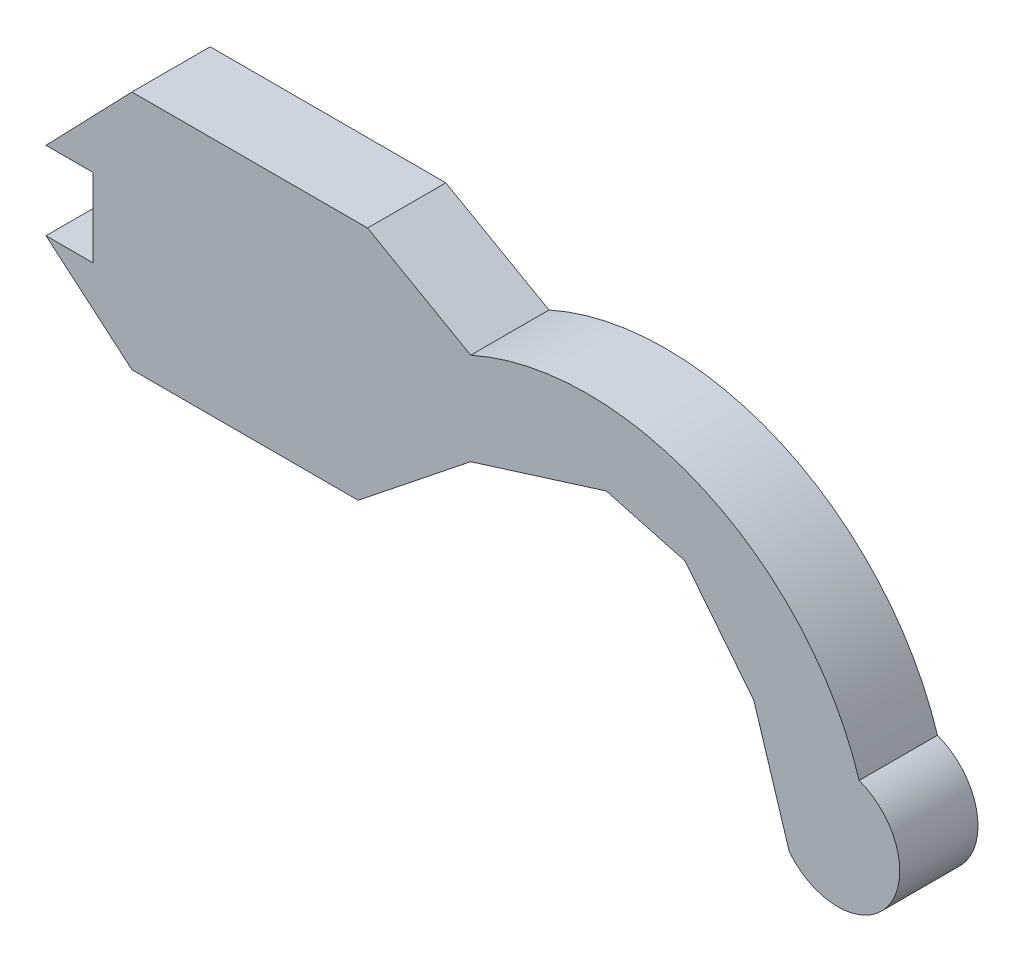
SolidWorks part; units mm, degrees
ref_plane "Front Plane" through (0, 0, 0) normal (0, 0, 1) x (1, 0, 0)
ref_plane "Top Plane" through (0, 0, 0) normal (0, 1, 0) x (1, 0, 0)
ref_plane "Right Plane" through (0, 0, 0) normal (1, 0, 0) x (0, 0, -1)
sketch "Sketch1" plane through (0, 0, 0) normal (0, 0, 1) x (1, 0, 0)
  line L0 (8.8809, 0) -> (7.9628, 0)
  line L1 (7.9628, 0) -> (9.6353, -1.4227)
  line L2 (9.6353, -1.4227) -> (14.04, -1.4227)
  line L3 (14.04, -1.4227) -> (16.2316, 0.3239)
  line L4 (16.2316, 0.3239) -> (18.8728, 1.1499)
  line L5 (18.8728, 1.1499) -> (20.4046, 0.7369)
  line L6 (20.4046, 0.7369) -> (21.7445, -0.9444)
  line L7 (21.7445, -0.9444) -> (22.4353, -3.1534)
  line L8 (8.8809, 0) -> (8.8809, 1.524)
  line L9 (8.8809, 1.524) -> (7.9628, 1.524)
  line L10 (7.9628, 1.524) -> (9.6353, 3.2601)
  line L11 (9.6353, 3.2601) -> (14.2232, 3.2601)
  line L12 (14.2232, 3.2601) -> (16.2316, 2.12)
  arc A0 (16.2316, 2.12) -> (23.7952, -1.2691) centre (18.5057, -2.9393) cw
  arc A1 (23.7952, -1.2691) -> (22.4353, -3.1534) centre (23.3783, -2.4011) cw
extrude "Boss-Extrude1" add sketch "Sketch1" along normal blind 1.524
